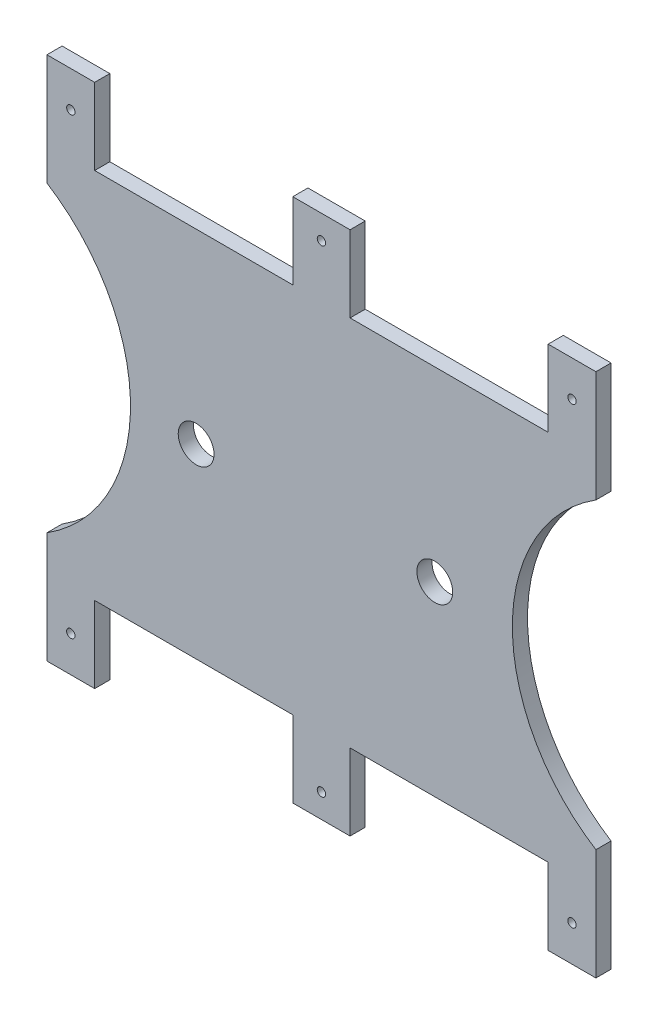
SolidWorks part; units mm, degrees
ref_plane "Front Plane" through (0, 0, 0) normal (0, 0, 1) x (1, 0, 0)
ref_plane "Top Plane" through (0, 0, 0) normal (0, 1, 0) x (1, 0, 0)
ref_plane "Right Plane" through (0, 0, 0) normal (1, 0, 0) x (0, 0, -1)
sketch "Sketch1" plane through (0, 0, 0) normal (0, 0, 1) x (1, 0, 0)
  line L3 (100, 110) -> (80, 110)
  line L8 (-110, 110) -> (-110, 78)
  line L9 (-110, 78) -> (-27, 78)
  line L10 (-27, 110) -> (-27, 78)
  line L11 (-3, 110) -> (-3, 78)
  line L12 (-3, 78) -> (80, 78)
  line L13 (80, 110) -> (80, 78)
  line L14 (-15, 100) -> (-15, -38) construction
  line L21 (-110, 110) -> (-130, 110)
  line L22 (-3, 110) -> (-27, 110)
  line L25 (0, 0) -> (-110, 0) construction
  line L58 (-130, 0) -> (-186.6797, 0) construction
  line L59 (-130, 110) -> (-130, 63.4429)
  line L60 (100, 110) -> (100, 63.4429)
  line L61 (-3, -110) -> (-27, -110)
  line L62 (-110, -110) -> (-130, -110)
  line L63 (80, -110) -> (80, -78)
  line L64 (-3, -78) -> (80, -78)
  line L65 (-3, -110) -> (-3, -78)
  line L66 (-27, -110) -> (-27, -78)
  line L67 (-110, -78) -> (-27, -78)
  line L68 (-110, -110) -> (-110, -78)
  line L69 (100, -110) -> (80, -110)
  line L70 (-130, -63.4429) -> (-130, -110)
  line L71 (100, -63.4429) -> (100, -110)
  circle A0 centre (32.5, 0) radius 7.5
  circle A1 centre (-67.5, 0) radius 7.5
  circle A2 centre (-120, 95) radius 1.7525
  circle A3 centre (90, 95) radius 1.7525
  circle A7 centre (-15, 100) radius 1.7525
  circle A8 centre (-15, -100) radius 1.7525
  circle A9 centre (90, -95) radius 1.7525
  circle A10 centre (-120, -95) radius 1.7525
  arc A11 (-130, -63.4429) -> (-130, 63.4429) centre (-170, 0) ccw
  arc A12 (100, -63.4429) -> (100, 63.4429) centre (140, 0) cw
  point P0 (0, 0)
  point P20 (-130, 0)
  point P21 (100, 0)
  point P62 (0, 0)
  point P63 (0, 0)
  point P64 (-173.1383, 0)
  dimension "D12" = 15
  dimension "D13" = 3.505
  dimension "D16" = 3.505
  dimension "D17" = 12
  dimension "D24" = 3.505
  dimension "D5" = 150
  dimension "D6" = 40
  dimension "D1" = 230
  dimension "D3" = 83
  dimension "D4" = 32
  dimension "D7" = 32
  dimension "D8" = 83
  dimension "D10" = 110
  dimension "D15" = 15
  dimension "D18" = 10
  dimension "D22" = 10
  dimension "D23" = 15
extrude "Boss-Extrude1" add sketch "Sketch1" along normal blind 6.35
